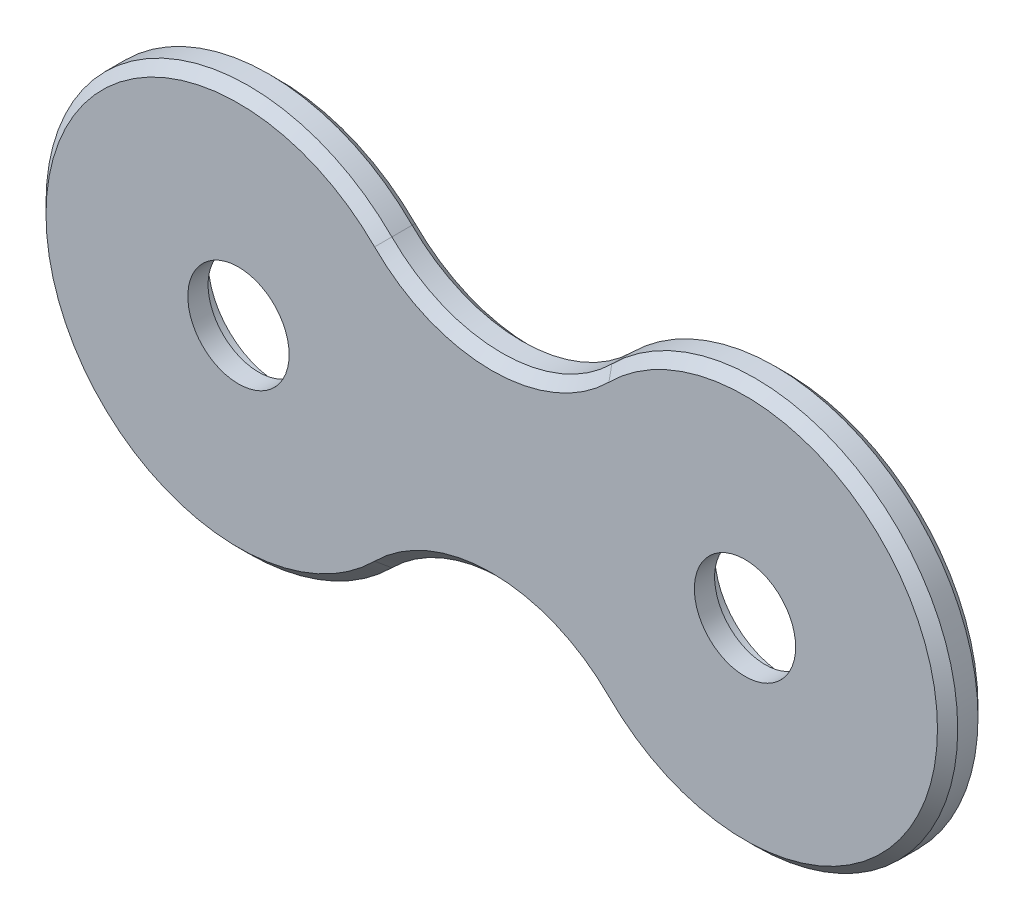
SolidWorks part; units mm, degrees
ref_plane "Front Plane" through (0, 0, 0) normal (0, 0, 1) x (1, 0, 0)
ref_plane "Top Plane" through (0, 0, 0) normal (0, 1, 0) x (1, 0, 0)
ref_plane "Right Plane" through (0, 0, 0) normal (1, 0, 0) x (0, 0, -1)
sketch "Sketch1" plane through (0, 0, 0) normal (0, 0, 1) x (1, 0, 0)
  arc A0 (17.9289, -7.0711) -> (17.9289, 7.0711) centre (25, 0) ccw
  circle A1 centre (25, 0) radius 2.5
  arc A2 (7.0711, 7.0711) -> (7.0711, -7.0711) centre (0, 0) ccw
  circle A3 centre (0, 0) radius 2.5
  arc A5 (7.0711, 7.0711) -> (17.9289, 7.0711) centre (12.5, 12.5) ccw
  arc A6 (17.9289, -7.0711) -> (7.0711, -7.0711) centre (12.5, -12.5) ccw
  dimension "D2" = 20
  dimension "D3" = 20
  dimension "D4" = 5
  dimension "D5" = 5
  dimension "D1" = 25
extrude "Boss-Extrude1" add sketch "Sketch1" along normal blind 2
chamfer "Chamfer1" distance 0.5 angle 45 8 edges at (-10, 0, 2) (12.5, -4.8223, 2) (35, 0, 2) (12.5, 4.8223, 2) (-10, 0, 0) (12.5, -4.8223, 0) (35, 0, 0) (12.5, 4.8223, 0)
sketch "Sketch2" plane through (0, 0, 0) normal (0, 0, 1) x (1, 0, 0)
  circle A0 centre (0, 0) radius 3.5
  circle A1 centre (25, 0) radius 3.5
  dimension "D1" = 7
  dimension "D2" = 7
extrude "Cut-Extrude1" cut sketch "Sketch2" along normal blind 1
